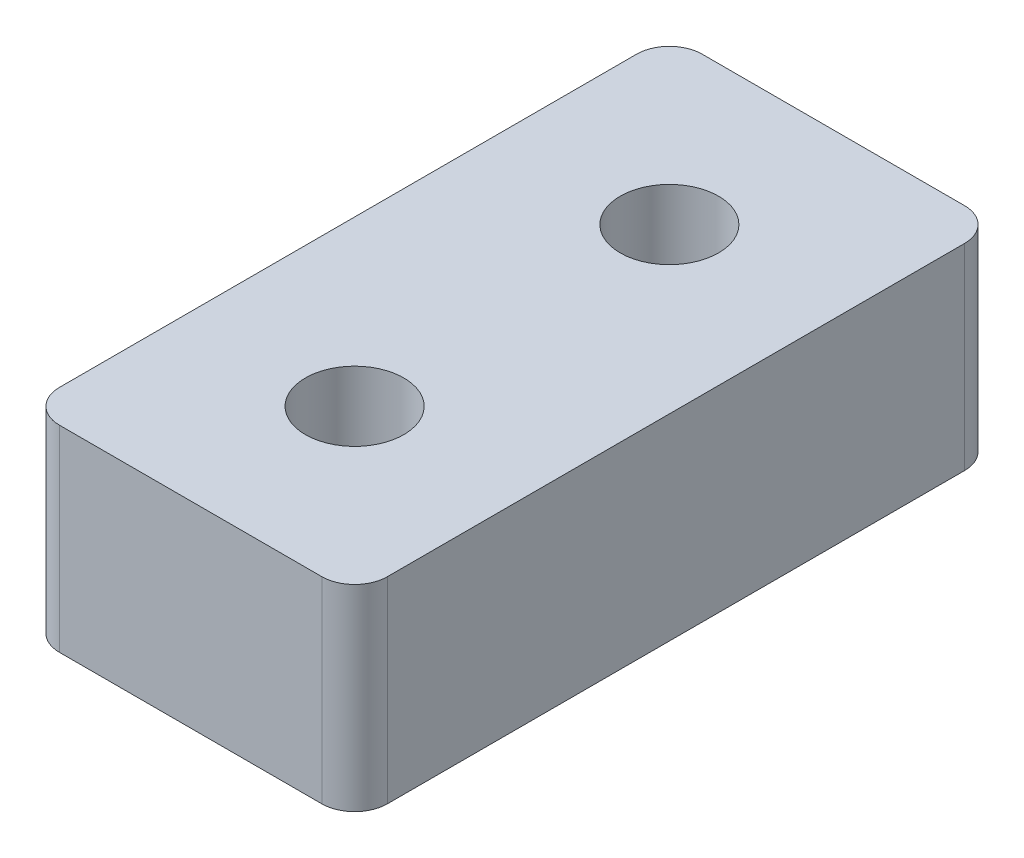
SolidWorks part; units mm, degrees
ref_plane "Front Plane" through (0, 0, 0) normal (0, 0, 1) x (1, 0, 0)
ref_plane "Top Plane" through (0, 0, 0) normal (0, 1, 0) x (1, 0, 0)
ref_plane "Right Plane" through (0, 0, 0) normal (1, 0, 0) x (0, 0, -1)
sketch "Sketch1" plane through (0, 0, 0) normal (0, 1, 0) x (1, 0, 0)
  line L0 (5, 14.6) -> (5, 5) construction
  line L1 (0, 0) -> (10, 0)
  line L2 (0, 0) -> (0, 19.6)
  line L3 (0, 19.6) -> (10, 19.6)
  line L4 (10, 0) -> (10, 19.6)
  line L5 (5, 5) -> (5, 0) construction
  line L6 (5, 9.8) -> (0, 9.8) construction
  circle A0 centre (5, 14.6) radius 1.5
  circle A1 centre (5, 5) radius 1.5
  dimension "D1" = 3
  dimension "D2" = 10
  dimension "D3" = 9.6
  dimension "D4" = 5
extrude "Boss-Extrude1" add sketch "Sketch1" along normal blind 6
fillet "Fillet1" radius 1 4 edges at (10, 3, -19.6) (10, 3, 0) (0, 3, 0) (0, 3, -19.6)
equation "\"housing_t\" = 6"
equation "\"M3_d\"= 3"
equation "\"D1@Sketch1\"=\"M3_d\""
equation "\"D1@Boss-Extrude1\"=\"housing_t\""
